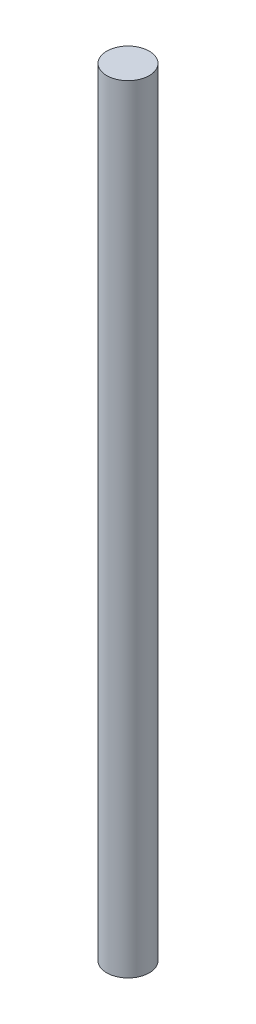
SolidWorks part; units mm, degrees
ref_plane "前视基准面" through (0, 0, 0) normal (0, 0, 1) x (1, 0, 0)
ref_plane "上视基准面" through (0, 0, 0) normal (0, 1, 0) x (1, 0, 0)
ref_plane "右视基准面" through (0, 0, 0) normal (1, 0, 0) x (0, 0, -1)
other "Configuration Table"
sketch "草图1" plane through (0, 0, 0) normal (0, 1, 0) x (1, 0, 0)
  circle A0 centre (0, 0) radius 4
  dimension "D1" = 8
extrude "凸台-拉伸1" add sketch "草图1" along normal blind 125
sketch "草图2" plane through (0, 0, 0) normal (0, -1, 0) x (1, 0, 0)
  circle A1 centre (0, 0) radius 4
  circle A2 centre (0, 0) radius 4
  dimension "D1" = 0
extrude "凸台-拉伸2" add sketch "草图2" along normal up to surface (21.39 mm away)
